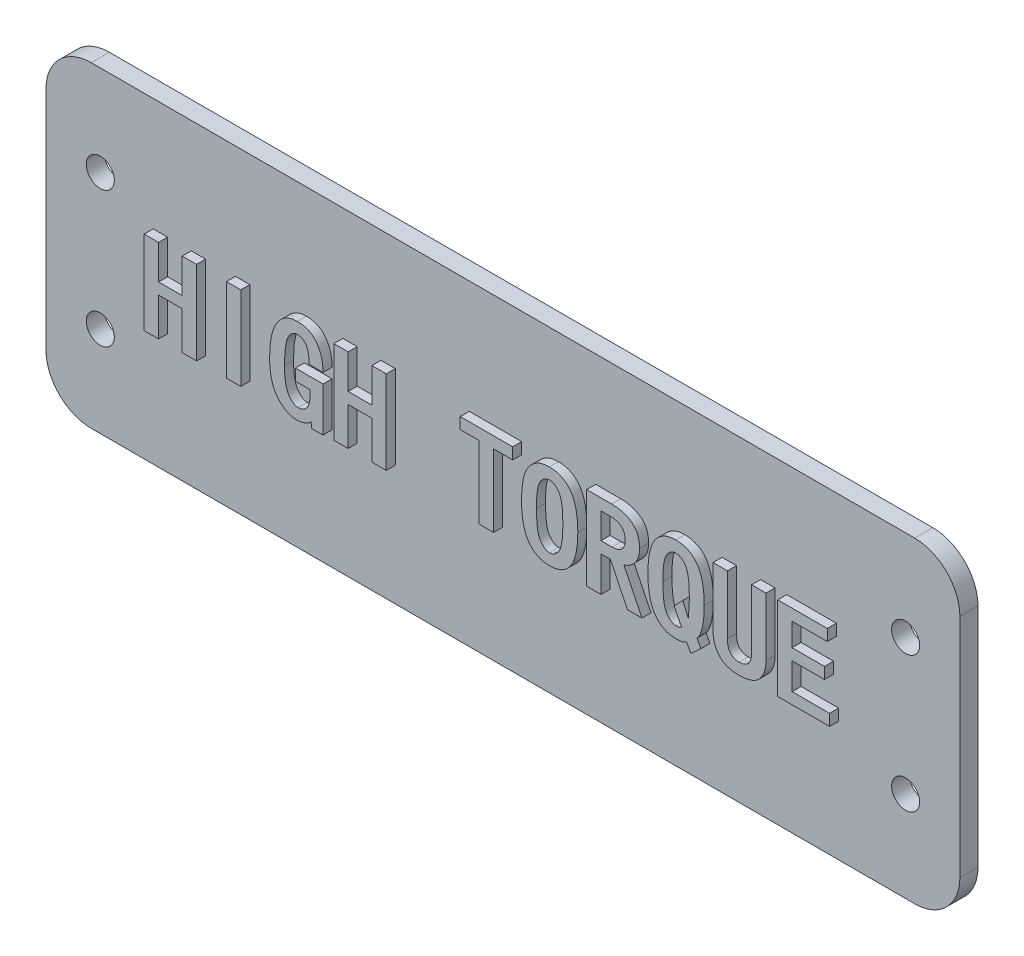
SolidWorks part; units mm, degrees
material "有机玻璃 (TM) GS 丙烯酸铸钣"
ref_plane "前视基准面" through (0, 0, 0) normal (0, 0, 1) x (1, 0, 0)
ref_plane "上视基准面" through (0, 0, 0) normal (0, 1, 0) x (1, 0, 0)
ref_plane "右视基准面" through (0, 0, 0) normal (1, 0, 0) x (0, 0, -1)
other "Configuration Table"
sketch "草图1" plane through (0, 0, 0) normal (0, 0, 1) x (1, 0, 0)
  line L1 (0, 0) -> (101, 0)
  line L2 (0, 0) -> (0, 35)
  line L3 (0, 35) -> (101, 35)
  line L4 (101, 0) -> (101, 35)
  circle A0 centre (6, 25) radius 1.55
  circle A7 centre (95, 25) radius 1.55
  circle A9 centre (95, 10) radius 1.55
  circle A10 centre (6, 10) radius 1.55
  dimension "D3" = 10
  dimension "D4" = 3.1
  dimension "D1" = 101
  dimension "D2" = 35
  dimension "D5" = 6
  dimension "D8" = 6
  dimension "D6" = 6
  dimension "D7" = 10
  dimension "D9" = 6
  dimension "D10" = 10
  dimension "D11" = 10
extrude "凸台-拉伸1" add sketch "草图1" along normal blind 2
fillet "圆角1" radius 5 4 edges at (101, 35, 1) (101, 0, 1) (0, 0, 1) (0, 35, 1)
sketch "草图3" plane through (0, 0, 2) normal (0, 0, 1) x (1, 0, 0)
  text T0 "HIGH TORQUE" font "黑体" height in points 36
extrude "凸台-拉伸2" add sketch "草图3" along normal blind 1
